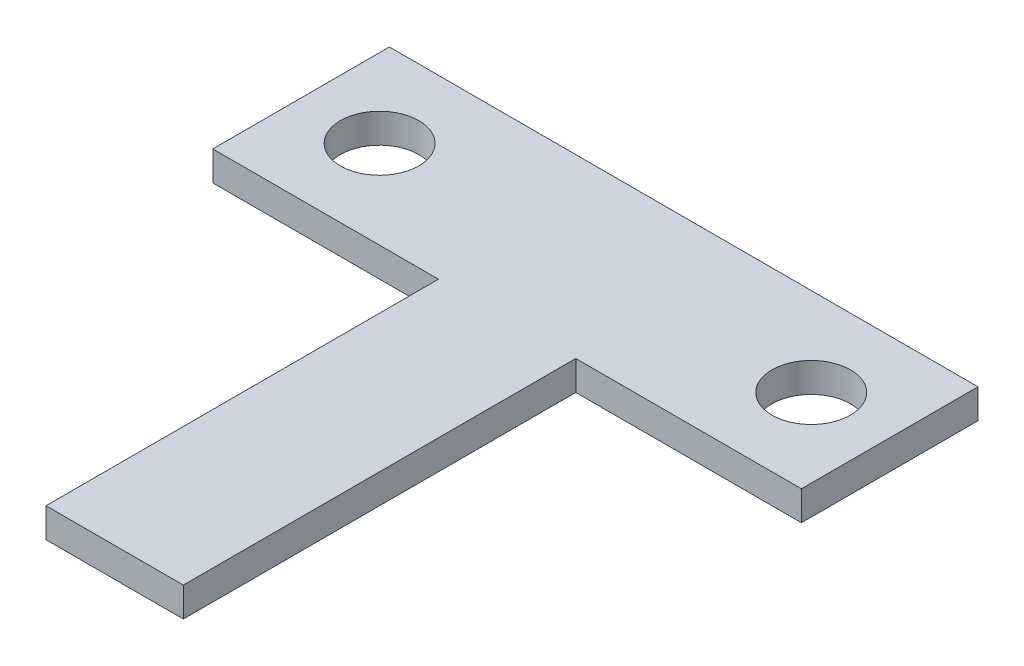
SolidWorks part; units mm, degrees
ref_plane "Plano frontal" through (0, 0, 0) normal (0, 0, 1) x (1, 0, 0)
ref_plane "Plano superior" through (0, 0, 0) normal (0, 1, 0) x (1, 0, 0)
ref_plane "Plano direito" through (0, 0, 0) normal (1, 0, 0) x (0, 0, -1)
sketch "Esboço1" plane through (0, 0, 0) normal (0, 1, 0) x (1, 0, 0)
  line L0 (-15, -4.5) -> (-15, 4.5)
  line L1 (-15, -4.5) -> (-3.5, -4.5)
  line L2 (-15, 4.5) -> (15, 4.5)
  line L3 (15, -4.5) -> (15, 4.5)
  line L4 (-15, -4.5) -> (15, 4.5) construction
  line L5 (-15, 4.5) -> (15, -4.5) construction
  line L6 (0, 4.5) -> (0, -23.8702) construction
  line L7 (3.5, -4.5) -> (15, -4.5)
  line L9 (-3.5, -4.5) -> (-3.5, -24.5)
  line L10 (-3.5, -24.5) -> (3.5, -24.5)
  line L11 (3.5, -4.5) -> (3.5, -24.5)
  circle A0 centre (11, 0) radius 2
  circle A1 centre (-11, 0) radius 2
  point P1 (0, 0)
  dimension "D6" = 4
  dimension "D1" = 30
  dimension "D2" = 9
  dimension "D3" = 20
  dimension "D4" = 7
  dimension "D5" = 11.5
  dimension "D7" = 4
  dimension "D8" = 4.5
extrude "Ressalto-extrusão1" add sketch "Esboço1" along normal blind 1.5
